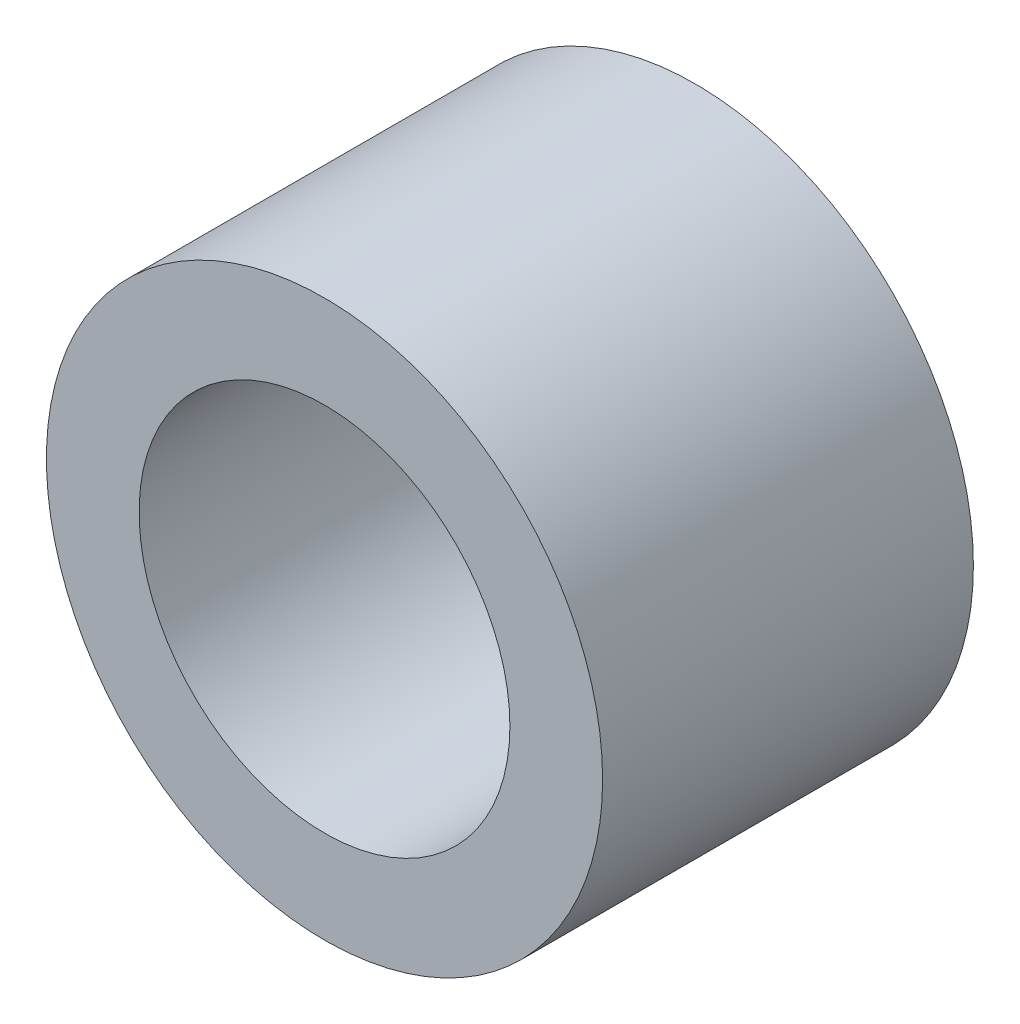
SolidWorks part; units mm, degrees
ref_plane "Front Plane" through (0, 0, 0) normal (0, 0, 1) x (1, 0, 0)
ref_plane "Top Plane" through (0, 0, 0) normal (0, 1, 0) x (1, 0, 0)
ref_plane "Right Plane" through (0, 0, 0) normal (1, 0, 0) x (0, 0, -1)
sketch "Sketch1" plane through (0, 0, 0) normal (0, 0, 1) x (1, 0, 0)
  circle A0 centre (0, 0) radius 5
  circle A1 centre (0, 0) radius 7.5
  dimension "D1" = 15
  dimension "D2" = 10
extrude "Boss-Extrude1" add sketch "Sketch1" along normal mid plane 10
